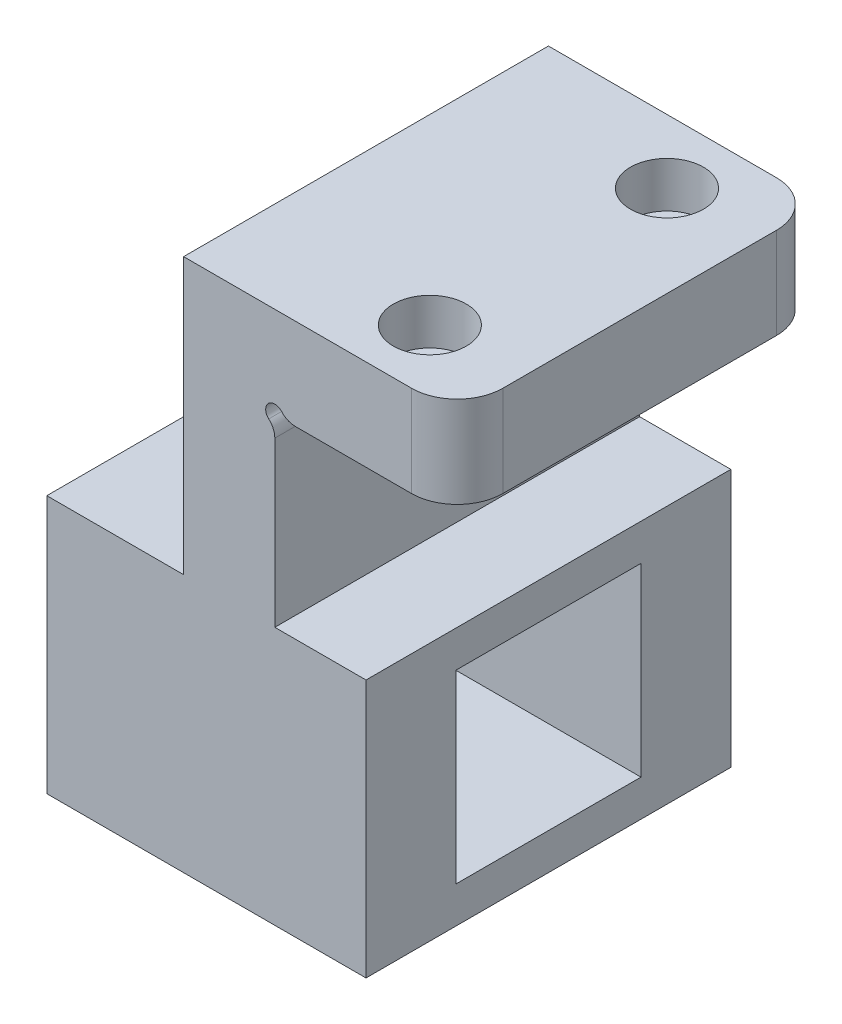
SolidWorks part; units mm, degrees
material "ABS"
ref_plane "Płaszczyzna przednia" through (0, 0, 0) normal (0, 0, 1) x (1, 0, 0)
ref_plane "Płaszczyzna górna" through (0, 0, 0) normal (0, 1, 0) x (1, 0, 0)
ref_plane "Płaszczyzna prawa" through (0, 0, 0) normal (1, 0, 0) x (0, 0, -1)
sketch "Szkic1" plane through (0, 0, 0) normal (0, 0, 1) x (1, 0, 0)
  line L0 (0, 0) -> (0, 19.7639)
  line L1 (2.2361, 22) -> (20, 22)
  line L2 (20, 22) -> (20, 32)
  line L3 (20, 32) -> (-10, 32)
  line L4 (-10, 32) -> (-10, 0)
  line L5 (-10, 0) -> (0, 0)
  arc A0 (0.7454, 22.6667) -> (-0.6667, 21.2546) centre (0, 22) ccw
  arc A1 (2.2361, 22) -> (0.7454, 22.6667) centre (2.2361, 24) cw
  arc A2 (0, 19.7639) -> (-0.6667, 21.2546) centre (-2, 19.7639) ccw
  dimension "D5" = 2
  dimension "D6" = 2
  dimension "D1" = 22
  dimension "D2" = 20
  dimension "D3" = 10
  dimension "D4" = 10
  dimension "D7" = 20
  dimension "D8" = 22
extrude "Dodanie-wyciągnięcie1" add sketch "Szkic1" along normal blind 40 contours L0 A2 A0 A1 L1 L2 L3 L4 L5
sketch "Szkic7" plane through (-10, 0, 0) normal (-1, 0, 0) x (0, 0, 1)
  line L4 (0, 19.7639) -> (0, 0)
  line L5 (40, 19.7639) -> (0, 19.7639)
  line L6 (40, 0) -> (40, 19.7639)
  line L7 (0, 0) -> (40, 0)
  line L8 (0, 19.7639) -> (0, 0)
  line L9 (40, 19.7639) -> (0, 19.7639)
  line L10 (40, 0) -> (40, 19.7639)
  line L11 (0, 0) -> (40, 0)
  circle A0 centre (20, 10) radius 4
  point P7 (20, 0)
  dimension "D2" = 8
  dimension "D3" = 10
  dimension "D1" = 0
extrude "Wytnij-wyciągnięcie2" cut sketch "Szkic7" against normal blind 5 contours A0
sketch "Szkic8" plane through (-5, 0, 0) normal (-1, 0, 0) x (0, 0, 1)
  circle A0 centre (20, 10) radius 4 construction
  circle A1 centre (20, 10) radius 4
  circle A2 centre (20, 10) radius 2.1
  dimension "D1" = 4.2
extrude "Wytnij-wyciągnięcie3" cut sketch "Szkic8" against normal blind 5 contours A2
sketch "Szkic9" plane through (0, 32, 0) normal (0, 1, 0) x (1, 0, 0)
  line L4 (20, 0) -> (2.2361, 0)
  line L5 (20, -40) -> (20, 0)
  line L6 (2.2361, -40) -> (20, -40)
  line L7 (2.2361, 0) -> (2.2361, -40)
  line L8 (20, 0) -> (2.2361, 0)
  line L9 (20, -40) -> (20, 0)
  line L10 (2.2361, -40) -> (20, -40)
  line L11 (2.2361, 0) -> (2.2361, -40)
  circle A0 centre (10, -7) radius 4
  circle A1 centre (10, -33) radius 4
  dimension "D3" = 8
  dimension "D2" = 10
  dimension "D4" = 7
  dimension "D5" = 7
  dimension "D1" = 0
extrude "Wytnij-wyciągnięcie4" cut sketch "Szkic9" against normal blind 5 contours A1 | A0
sketch "Szkic10" plane through (0, 27, 0) normal (0, 1, 0) x (1, 0, 0)
  circle A0 centre (10, -7) radius 4 construction
  circle A1 centre (10, -33) radius 4 construction
  circle A2 centre (10, -7) radius 4
  circle A3 centre (10, -33) radius 4
  circle A4 centre (10, -7) radius 2.1
  circle A5 centre (10, -33) radius 2.1
  dimension "D1" = 4.2
extrude "Wytnij-wyciągnięcie5" cut sketch "Szkic10" against normal blind 5 contours A5 | A4
fillet "Zaokrąglenie1" radius 5 2 edges at (20, 27, 0) (20, 27, 40)
ref_plane "Płaszczyzna1" through (0, 0, 20) normal (0, 0, 1) x (1, 0, 0)
sketch "Sketch1" plane through (-10, 0, 0) normal (-1, 0, 0) x (0, 0, 1)
  line L0 (20, 64.3239) -> (20, 19.1441) construction
  line L1 (9.85, -2.2) -> (30.15, -2.2)
  line L2 (9.85, -2.2) -> (9.85, -22.5)
  line L3 (9.85, -22.5) -> (30.15, -22.5)
  line L4 (30.15, -2.2) -> (30.15, -22.5)
  line L5 (0, 32) -> (0, 0) construction
  line L6 (40, 32) -> (40, 0) construction
  line L7 (40, 22) -> (0, 22) construction
  line L8 (0, 1.8) -> (40, 1.8)
  line L9 (40, 1.8) -> (40, -26.5)
  line L10 (0, -26.5) -> (40, -26.5)
  line L11 (0, 1.8) -> (0, -26.5)
  line L13 (40, 22) -> (0, 22)
  dimension "D1" = 20.3
  dimension "D2" = 20.3
  dimension "D3" = 28.3
  dimension "D4" = 4
  dimension "D5" = 20.2
extrude "Boss-Extrude1" add sketch "Sketch1" along normal blind 15 and the other way blind 20.0001 contours L8 L9 L10 L11 | L1 L4 L3 L2
